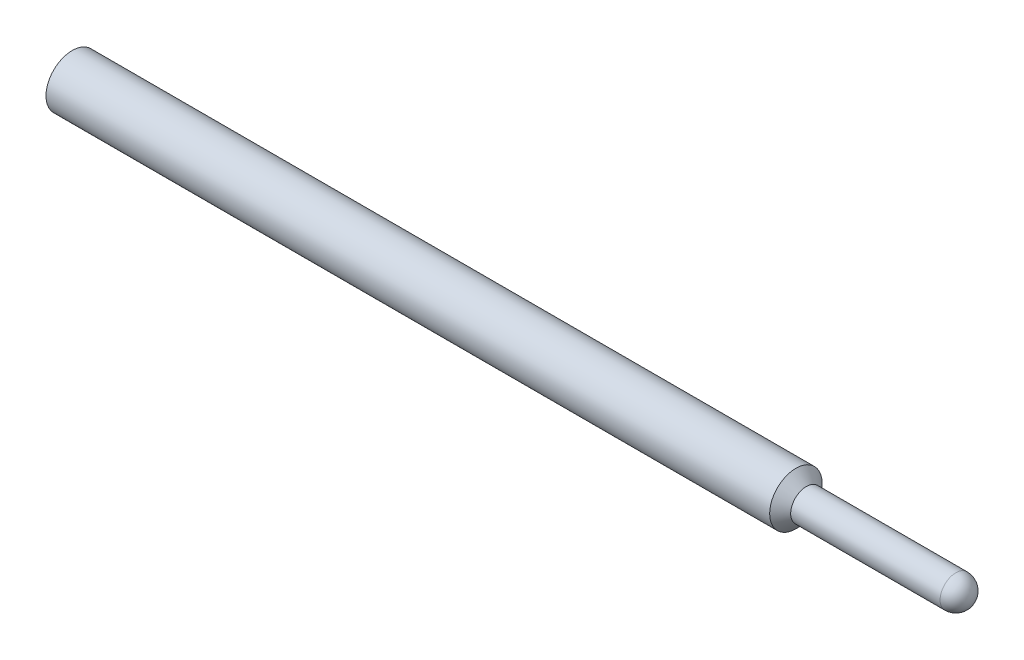
SolidWorks part; units mm, degrees
ref_plane "Front Plane" through (0, 0, 0) normal (0, 0, 1) x (1, 0, 0)
ref_plane "Top Plane" through (0, 0, 0) normal (0, 1, 0) x (1, 0, 0)
ref_plane "Right Plane" through (0, 0, 0) normal (1, 0, 0) x (0, 0, -1)
sketch "Sketch1" plane through (0, 0, 0) normal (0, 0, 1) x (1, 0, 0)
  line L0 (0, 0) -> (337, 0) construction
  line L1 (0, 0) -> (0, 10)
  line L2 (0, 10) -> (276, 10)
  line L3 (276, 10) -> (280, 6)
  line L4 (280, 6) -> (337, 6)
  line L5 (337, 0) -> (343, 0) construction
  line L6 (280, 6) -> (280, 12.9756) construction
  line L7 (0, 0) -> (343, 0)
  arc A0 (337, 6) -> (343, 0) centre (337, 0) cw
  dimension "D1" = 6
  dimension "D2" = 63
  dimension "D3" = 45
  dimension "D4" = 10
  dimension "D5" = 280
revolve "Revolve1" add sketch "Sketch1" angle 360 about L7
